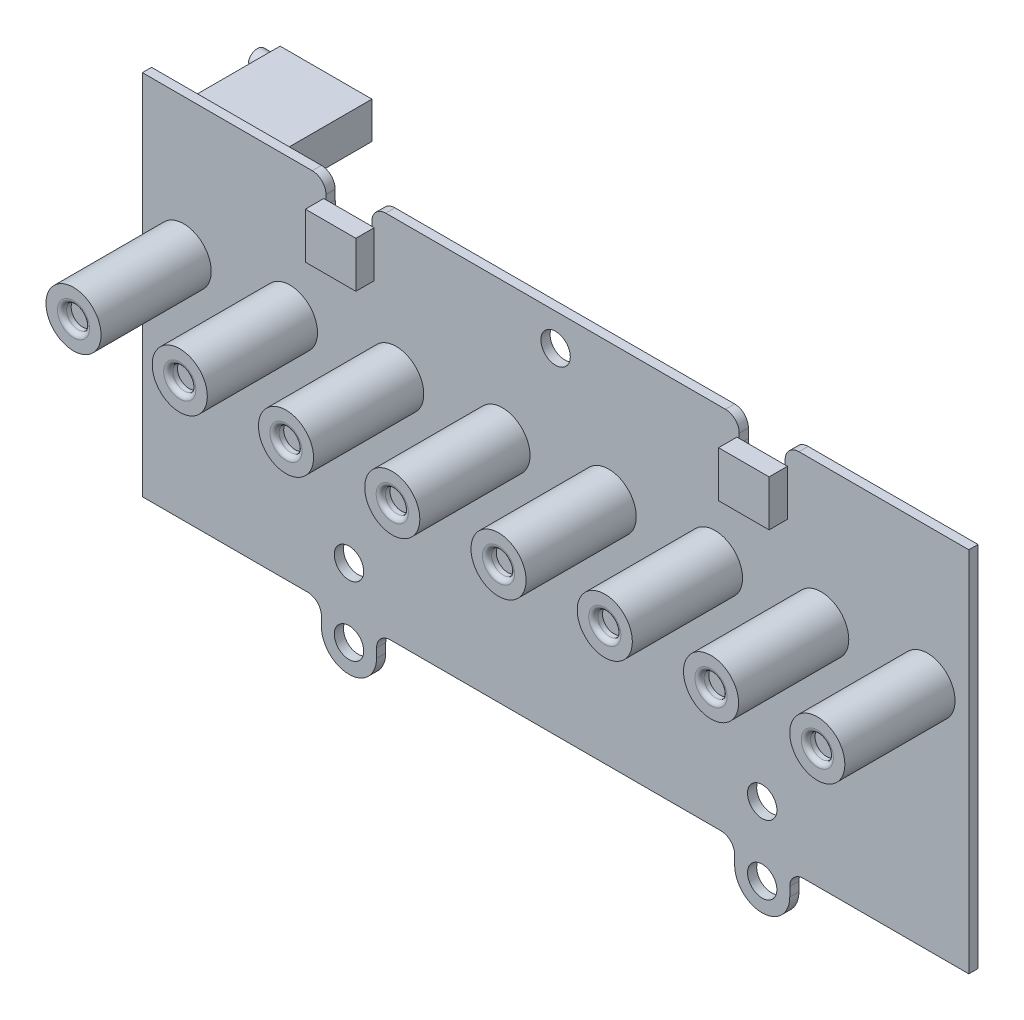
SolidWorks part; units mm, degrees
ref_plane "前视基准面" through (0, 0, 0) normal (0, 0, 1) x (1, 0, 0)
ref_plane "上视基准面" through (0, 0, 0) normal (0, 1, 0) x (1, 0, 0)
ref_plane "右视基准面" through (0, 0, 0) normal (1, 0, 0) x (0, 0, -1)
sketch "草图1" plane through (0, 0, 0) normal (0, 0, 1) x (1, 0, 0)
  line L0 (-22.5, -15) -> (22.5, -15) construction
  line L1 (45, -20) -> (25.5, -20)
  line L2 (45, -20) -> (45, 20)
  line L3 (45, 20) -> (25, 20)
  line L4 (-45, -20) -> (-45, 20)
  line L5 (45, -20) -> (-45, 20) construction
  line L6 (45, 20) -> (-45, -20) construction
  line L7 (0, 16.5) -> (0, -15) construction
  line L8 (0, 20) -> (0, 16.5) construction
  line L9 (-25.5, -20) -> (-25.5, -22.5)
  line L10 (-19.5, -22.5) -> (-19.5, -20)
  line L11 (-22.5, -15) -> (-22.5, -22.5) construction
  line L12 (-25.5, -20) -> (-45, -20)
  line L13 (22.5, -15) -> (22.5, -22.5) construction
  line L14 (19.5, -22.5) -> (19.5, -20)
  line L15 (25.5, -20) -> (25.5, -22.5)
  line L16 (19.5, -20) -> (-19.5, -20)
  line L17 (-22.5, -15) -> (-22.5, 20) construction
  line L18 (-25, 20) -> (-25, 17.5)
  line L19 (-20, 17.5) -> (-20, 20)
  line L20 (-25, 20) -> (-45, 20)
  line L21 (-25, 20) -> (-20, 20) construction
  line L22 (22.5, -15) -> (22.5, 15) construction
  line L23 (20, 17.5) -> (20, 20)
  line L24 (25, 20) -> (25, 17.5)
  line L25 (20, 20) -> (-20, 20)
  circle A0 centre (0, 16.5) radius 1.6
  circle A1 centre (-22.5, -15) radius 1.6
  circle A2 centre (22.5, -15) radius 1.6
  arc A3 (-25.5, -22.5) -> (-19.5, -22.5) centre (-22.5, -22.5) ccw
  circle A4 centre (-22.5, -22.5) radius 1.6
  circle A5 centre (22.5, -22.5) radius 1.6
  arc A6 (25.5, -22.5) -> (19.5, -22.5) centre (22.5, -22.5) cw
  arc A7 (-25, 17.5) -> (-20, 17.5) centre (-22.5, 17.5) ccw
  arc A8 (25, 17.5) -> (20, 17.5) centre (22.5, 17.5) cw
  point P0 (0, 0)
  dimension "D3" = 3.2
  dimension "D7" = 7.5
  dimension "D6" = 5
  dimension "D1" = 90
  dimension "D2" = 40
  dimension "D4" = 3.5
  dimension "D5" = 45
  dimension "D8" = 6
  dimension "D9" = 5
  dimension "D10" = 2.5
  dimension "D11" = 2.5
extrude "凸台-拉伸1" add sketch "草图1" along normal blind 1
fillet "圆角2" radius 1.5 8 edges at (-25.5, -20, 0.5) (-19.5, -20, 0.5) (19.5, -20, 0.5) (25.5, -20, 0.5) (25, 20, 0.5) (20, 20, 0.5) (-20, 20, 0.5) (-25, 20, 0.5)
sketch "草图2" plane through (0, 0, 1) normal (0, 0, 1) x (1, 0, 0)
  line L0 (-22.5, 15.5) -> (-22.5, 15) construction
  line L1 (-25.25, 18) -> (-19.75, 18)
  line L2 (-25.25, 18) -> (-25.25, 13)
  line L3 (-25.25, 13) -> (-19.75, 13)
  line L4 (-19.75, 18) -> (-19.75, 13)
  line L5 (-25.25, 18) -> (-19.75, 13) construction
  line L6 (-25.25, 13) -> (-19.75, 18) construction
  line L7 (-26.5, 20) -> (-45, 20) construction
  arc A0 (-25, 17.5) -> (-20, 17.5) centre (-22.5, 17.5) ccw construction
  point P4 (-22.5, 15.5)
  dimension "D1" = 5.5
  dimension "D2" = 5
  dimension "D3" = 2
extrude "凸台-拉伸7" add sketch "草图2" along normal blind 2
mirror "镜向1" about plane through (0, 0, 0) normal (1, 0, 0) of "凸台-拉伸7"
sketch "草图3" plane through (0, 0, 1) normal (0, 0, 1) x (1, 0, 0)
  line L0 (-45, 5) -> (45, 5) construction
  line L1 (-45, 20) -> (-45, -20) construction
  line L2 (45, -20) -> (45, 20) construction
  line L3 (-26.5, 20) -> (-45, 20) construction
  circle A0 centre (-40.5, 5) radius 3
  circle A1 centre (-28.9286, 5) radius 3
  circle A2 centre (-17.3571, 5) radius 3
  circle A3 centre (-5.7857, 5) radius 3
  circle A4 centre (5.7857, 5) radius 3
  circle A5 centre (17.3571, 5) radius 3
  circle A6 centre (28.9286, 5) radius 3
  circle A7 centre (40.5, 5) radius 3
  dimension "D4" = 4.5
  dimension "D5" = 6
  dimension "D1" = 15
  dimension "D3" = 4.5
  dimension "D2" = 8
extrude "凸台-拉伸8" add sketch "草图3" along normal blind 12
sketch "草图4" plane through (0, 0, 13) normal (0, 0, 1) x (1, 0, 0)
  circle A0 centre (-40.5, 5) radius 1.25
  circle A1 centre (-28.9286, 5) radius 1.25
  circle A2 centre (-17.3571, 5) radius 1.25
  circle A3 centre (-5.7857, 5) radius 1.25
  circle A4 centre (5.7857, 5) radius 1.25
  circle A5 centre (17.3571, 5) radius 1.25
  circle A6 centre (28.9286, 5) radius 1.25
  circle A7 centre (40.5, 5) radius 1.25
  dimension "D1" = 2.5
extrude "切除-拉伸1" cut sketch "草图4" against normal blind 1
fillet "圆角3" radius 0.5 8 edges at (41.75, 5, 13) (30.1786, 5, 13) (18.6071, 5, 13) (7.0357, 5, 13) (-4.5357, 5, 13) (-16.1071, 5, 13) (-27.6786, 5, 13) (-39.25, 5, 13)
sketch "草图5" plane through (0, 0, 0) normal (0, 0, -1) x (-1, 0, 0)
  line L0 (26.5, 20) -> (45, 20) construction
  line L1 (31, 19) -> (41, 19)
  line L2 (31, 19) -> (31, 15)
  line L3 (31, 15) -> (41, 15)
  line L4 (41, 19) -> (41, 15)
  line L5 (31, 19) -> (41, 15) construction
  line L6 (31, 15) -> (41, 19) construction
  line L7 (45, 20) -> (45, -20) construction
  point P4 (36, 17)
  dimension "D1" = 1
  dimension "D2" = 4
  dimension "D3" = 10
  dimension "D4" = 4
extrude "凸台-拉伸9" add sketch "草图5" along normal blind 10
sketch "草图6" plane through (-41, 0, 0) normal (-1, 0, 0) x (0, 0, 1)
  circle A0 centre (-8.7261, 17.8102) radius 1
  dimension "D1" = 2
extrude "凸台-拉伸10" add sketch "草图6" along normal blind 1.2
sketch "草图7" plane through (-42.2, 0, 0) normal (-1, 0, 0) x (0, 0, 1)
  line L0 (-9.6774, 18.1183) -> (-7.7301, 17.8996)
  line L1 (-9.7221, 17.7208) -> (-7.7747, 17.5021)
  circle A0 centre (-8.7261, 17.8102) radius 1 construction
  arc A1 (-9.6774, 18.1183) -> (-9.7216, 17.7163) centre (-8.7261, 17.8102) ccw
  arc A2 (-7.7301, 17.8996) -> (-7.7786, 17.4903) centre (-8.7261, 17.8102) cw
  circle A3 centre (-8.7261, 17.8102) radius 1 construction
  circle M3 centre (-8.7261, 17.8102) radius 1
  dimension "D1" = 0.2
extrude "切除-拉伸2" cut sketch "草图7" against normal blind 0.1 contours L1 L0 M3
sketch "草图8" plane through (0, 0, 0) normal (0, 0, -1) x (-1, 0, 0)
  line L0 (-45, -8) -> (45, -8) construction
  line L1 (-45, -20) -> (-45, 20) construction
  line L2 (45, 20) -> (45, -20) construction
  line L3 (18, -20) -> (-18, -20) construction
  line L5 (-16, -8) -> (-6, -8)
  line L6 (-16, -8) -> (-16, -4)
  line L7 (-16, -4) -> (-6, -4)
  line L8 (-6, -8) -> (-6, -4)
  line L9 (-16, -8) -> (-6, -4) construction
  line L10 (-16, -4) -> (-6, -8) construction
  line L11 (-1, -8) -> (5, -8)
  line L12 (-1, -8) -> (-1, -4)
  line L13 (-1, -4) -> (5, -4)
  line L14 (5, -8) -> (5, -4)
  line L15 (-1, -8) -> (5, -4) construction
  line L16 (-1, -4) -> (5, -8) construction
  line L17 (12, -8) -> (22, -8)
  line L18 (12, -8) -> (12, -4)
  line L19 (12, -4) -> (22, -4)
  line L20 (22, -8) -> (22, -4)
  line L21 (12, -8) -> (22, -4) construction
  line L22 (12, -4) -> (22, -8) construction
  point P12 (-11, -6)
  point P17 (2, -6)
  point P18 (-1, -6)
  point P23 (17, -6)
  dimension "D1" = 12
  dimension "D2" = 4
  dimension "D3" = 10
  dimension "D4" = 29
  dimension "D5" = 44
  dimension "D6" = 6
  dimension "D7" = 33
  dimension "D8" = 10
extrude "凸台-拉伸11" add sketch "草图8" along normal blind 2
sketch "草图10" plane through (0, 0, 0) normal (0, 0, -1) x (-1, 0, 0)
  line L0 (-6, -4) -> (-16, -4) construction
  line L1 (-30, -4) -> (-20, -4) construction
  line L2 (-30, -4.625) -> (-30, -7.375)
  line L3 (-30, -8) -> (-20, -8) construction
  line L4 (-20, -4.625) -> (-20, -7.375)
  line L5 (-30, -4) -> (-20, -8) construction
  line L6 (-30, -8) -> (-20, -4) construction
  line L11 (30, -4) -> (40, -4) construction
  line L12 (30, -4.625) -> (30, -7.375)
  line L16 (-16, -8) -> (-6, -8) construction
  line L17 (-45, -20) -> (-45, 20) construction
  line L19 (-30, -4.625) -> (-29.375, -4)
  line L20 (-28.125, -4) -> (-27.5, -4.625)
  line L21 (-27.5, -4.625) -> (-26.875, -4)
  line L22 (-25.625, -4) -> (-25, -4.625)
  line L23 (-25, -4.625) -> (-24.375, -4)
  line L24 (-23.125, -4) -> (-22.5, -4.625)
  line L25 (-22.5, -4.625) -> (-21.875, -4)
  line L26 (-20.625, -4) -> (-20, -4.625)
  line L27 (-29.375, -4) -> (-28.125, -4)
  line L28 (-26.875, -4) -> (-25.625, -4)
  line L29 (-24.375, -4) -> (-23.125, -4)
  line L30 (-20.625, -4) -> (-21.875, -4)
  line L31 (-30, -4.625) -> (-27.5, -4.625) construction
  line L32 (-27.5, -4.625) -> (-25, -4.625) construction
  line L33 (-25, -4.625) -> (-21.8112, -4.625) construction
  line L34 (-21.8112, -4.625) -> (-20, -4.625) construction
  line L35 (-30, -6) -> (-20, -6) construction
  line L36 (-30, -7.375) -> (-29.375, -8)
  line L37 (-20.625, -8) -> (-20, -7.375)
  line L38 (-25, -7.375) -> (-21.8112, -7.375) construction
  line L39 (-27.5, -7.375) -> (-25, -7.375) construction
  line L40 (-20.625, -8) -> (-21.875, -8)
  line L41 (-24.375, -8) -> (-23.125, -8)
  line L42 (-26.875, -8) -> (-25.625, -8)
  line L43 (-29.375, -8) -> (-28.125, -8)
  line L44 (-22.5, -7.375) -> (-21.875, -8)
  line L45 (-23.125, -8) -> (-22.5, -7.375)
  line L46 (-25, -7.375) -> (-24.375, -8)
  line L47 (-25.625, -8) -> (-25, -7.375)
  line L48 (-27.5, -7.375) -> (-26.875, -8)
  line L49 (-28.125, -8) -> (-27.5, -7.375)
  line L50 (-30, -8) -> (-30, -4) construction
  line L51 (-20, -4) -> (-20, -8) construction
  line L52 (30, -8) -> (40, -8) construction
  line L53 (40, -4.625) -> (40, -7.375)
  line L54 (30, -4) -> (40, -8) construction
  line L55 (30, -8) -> (40, -4) construction
  line L56 (30, -4.625) -> (30.625, -4)
  line L57 (31.875, -4) -> (32.5, -4.625)
  line L58 (32.5, -4.625) -> (33.125, -4)
  line L59 (34.375, -4) -> (35, -4.625)
  line L60 (35, -4.625) -> (35.625, -4)
  line L61 (36.875, -4) -> (37.5, -4.625)
  line L62 (37.5, -4.625) -> (38.125, -4)
  line L63 (39.375, -4) -> (40, -4.625)
  line L64 (30.625, -4) -> (31.875, -4)
  line L65 (33.125, -4) -> (34.375, -4)
  line L66 (35.625, -4) -> (36.875, -4)
  line L67 (39.375, -4) -> (38.125, -4)
  line L68 (30, -4.625) -> (32.5, -4.625) construction
  line L69 (32.5, -4.625) -> (35, -4.625) construction
  line L70 (35, -4.625) -> (39.9467, -4.625) construction
  line L71 (39.9467, -4.625) -> (40, -4.625) construction
  line L72 (30, -6) -> (40, -6) construction
  line L73 (30, -7.375) -> (30.625, -8)
  line L74 (39.375, -8) -> (40, -7.375)
  line L75 (35, -7.375) -> (39.9467, -7.375) construction
  line L76 (32.5, -7.375) -> (35, -7.375) construction
  line L77 (39.375, -8) -> (38.125, -8)
  line L78 (35.625, -8) -> (36.875, -8)
  line L79 (33.125, -8) -> (34.375, -8)
  line L80 (30.625, -8) -> (31.875, -8)
  line L81 (37.5, -7.375) -> (38.125, -8)
  line L82 (36.875, -8) -> (37.5, -7.375)
  line L83 (35, -7.375) -> (35.625, -8)
  line L84 (34.375, -8) -> (35, -7.375)
  line L85 (32.5, -7.375) -> (33.125, -8)
  line L86 (31.875, -8) -> (32.5, -7.375)
  line L87 (30, -8) -> (30, -4) construction
  line L88 (40, -4) -> (40, -8) construction
  line L89 (45, 20) -> (45, -20) construction
  line L90 (-27, -20) -> (-45, -20) construction
  line L91 (45, -20) -> (27, -20) construction
  point P4 (-25, -6)
  point P9 (35, -6)
  point P78 (35, -4.812)
  point P79 (30, -4.6457)
  point P80 (40, -4.6225)
  point P81 (39.9467, -3.4404)
  dimension "D1" = 10
  dimension "D2" = 15
  dimension "D3" = 10
  dimension "D4" = 45
  dimension "D5" = 1.25
  dimension "D6" = 0.625
  dimension "D7" = 0.625
  dimension "D8" = 1.25
  dimension "D9" = 45
  dimension "D10" = 0.625
  dimension "D11" = 0.625
  dimension "D12" = 5
  dimension "D13" = 12
  dimension "D14" = 12
  dimension "D15" = 4
  dimension "D16" = 4
extrude "凸台-拉伸12" add sketch "草图10" along normal blind 3
sketch "草图11" plane through (0, 0, -3) normal (0, 0, -1) x (-1, 0, 0)
  line L0 (-28.75, -4) -> (-28.75, -8) construction
  line L1 (-28.75, -5.25) -> (-21.25, -5.25) construction
  line L2 (-28.75, -5.25) -> (-28.75, -6.75) construction
  line L3 (-28.75, -6.75) -> (-21.25, -6.75) construction
  line L4 (-21.25, -5.25) -> (-21.25, -6.75) construction
  line L5 (-28.75, -5.25) -> (-21.25, -6.75) construction
  line L6 (-28.75, -6.75) -> (-21.25, -5.25) construction
  line L7 (-28.125, -4) -> (-29.375, -4) construction
  line L8 (-29.375, -8) -> (-28.125, -8) construction
  line L9 (-28.75, -4) -> (-28.75, -6) construction
  line L10 (-21.25, -4) -> (-21.25, -6) construction
  line L11 (-20.625, -4) -> (-21.875, -4) construction
  line L12 (-26.25, -4) -> (-26.25, -5.25) construction
  line L13 (-25.625, -4) -> (-26.875, -4) construction
  line L14 (-30, -6) -> (-28.75, -6) construction
  line L16 (-30, -4.625) -> (-30, -7.375) construction
  line L17 (-21.25, -5.25) -> (-21.25, -6.75) construction
  line L18 (-21.25, -6.75) -> (-21.25, -5.25) construction
  line L19 (-23.75, -5.25) -> (-23.75, -4) construction
  line L20 (-23.125, -4) -> (-24.375, -4) construction
  line L21 (-28.75, -6) -> (-21.25, -6) construction
  line L22 (31.25, -5.25) -> (38.75, -5.25) construction
  line L23 (31.25, -5.25) -> (31.25, -6.75) construction
  line L24 (31.25, -6.75) -> (38.75, -6.75) construction
  line L25 (38.75, -5.25) -> (38.75, -6.75) construction
  line L26 (31.25, -5.25) -> (38.75, -6.75) construction
  line L27 (31.25, -6.75) -> (38.75, -5.25) construction
  line L28 (38.75, -5.25) -> (38.75, -6.75) construction
  line L29 (38.75, -6.75) -> (38.75, -5.25) construction
  line L30 (31.25, -6) -> (38.75, -6) construction
  line L31 (30, -6) -> (31.25, -6) construction
  line L32 (30, -4.625) -> (30, -7.375) construction
  line L33 (31.25, -4) -> (31.25, -5.25) construction
  line L34 (31.875, -4) -> (30.625, -4) construction
  line L35 (33.75, -4) -> (33.75, -5.25) construction
  line L36 (34.375, -4) -> (33.125, -4) construction
  line L37 (36.25, -5.25) -> (36.25, -4) construction
  line L38 (36.875, -4) -> (35.625, -4) construction
  line L39 (38.75, -4) -> (38.75, -5.25) construction
  line L40 (39.375, -4) -> (38.125, -4) construction
  circle A0 centre (-28.75, -5.25) radius 0.25
  circle A1 centre (-26.25, -5.25) radius 0.25
  circle A2 centre (-23.75, -5.25) radius 0.25
  circle A3 centre (-21.25, -5.25) radius 0.25
  circle A8 centre (-21.25, -6.75) radius 0.25
  circle A9 centre (-23.75, -6.75) radius 0.25
  circle A10 centre (-26.25, -6.75) radius 0.25
  circle A11 centre (-28.75, -6.75) radius 0.25
  circle A12 centre (31.25, -5.25) radius 0.25
  circle A13 centre (33.75, -5.25) radius 0.25
  circle A14 centre (36.25, -5.25) radius 0.25
  circle A15 centre (38.75, -5.25) radius 0.25
  circle A16 centre (38.75, -6.75) radius 0.25
  circle A17 centre (36.25, -6.75) radius 0.25
  circle A18 centre (33.75, -6.75) radius 0.25
  circle A19 centre (31.25, -6.75) radius 0.25
  point P10 (-25, -6)
  point P48 (35, -6)
  point P69 (38.75, -6.75)
  dimension "D1" = 0.5
  dimension "D5" = 0.5
  dimension "D2" = 90
  dimension "D3" = 1.5
  dimension "D4" = 1.5
extrude "凸台-拉伸13" add sketch "草图11" along normal blind 7
